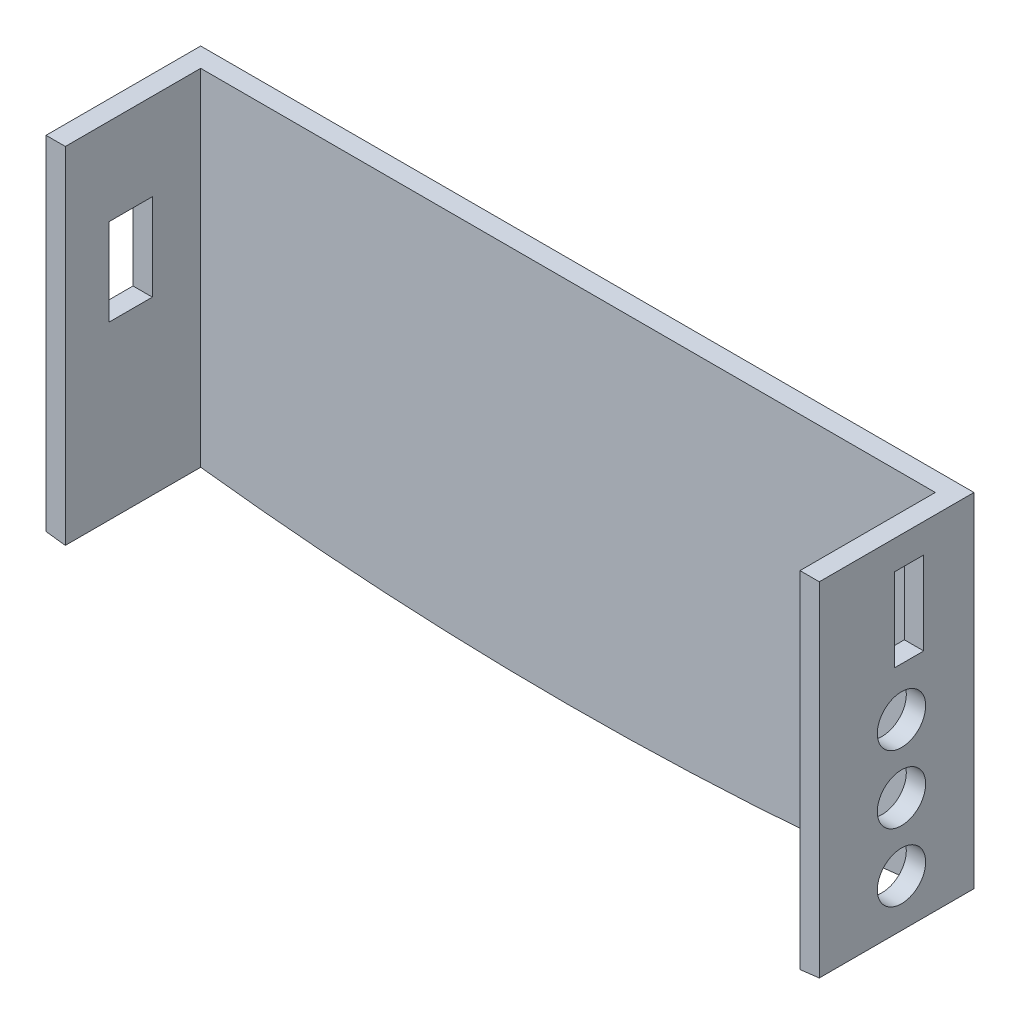
SolidWorks part; units mm, degrees
ref_plane "前视基准面" through (0, 0, 0) normal (0, 0, 1) x (1, 0, 0)
ref_plane "上视基准面" through (0, 0, 0) normal (0, 1, 0) x (1, 0, 0)
ref_plane "右视基准面" through (0, 0, 0) normal (1, 0, 0) x (0, 0, -1)
other "Configuration Table"
sketch "草图1" plane through (0, 0, 0) normal (0, 0, 1) x (1, 0, 0)
  line L1 (-10.4206, -29.1673) -> (-90.4206, -29.1673)
  line L2 (-10.4206, -29.1673) -> (-10.4206, 6.3327)
  line L3 (-10.4206, 6.3327) -> (-90.4206, 6.3327)
  line L4 (-90.4206, -29.1673) -> (-90.4206, 6.3327)
  line L5 (-10.4206, -29.1673) -> (-90.4206, 6.3327) construction
  line L6 (-10.4206, 6.3327) -> (-90.4206, -29.1673) construction
  arc A0 (-90.4206, -29.1673) -> (-10.4206, -29.1673) centre (-50.4206, 290.0866) ccw
  point P0 (-50.4206, -11.4173)
  dimension "D3" = 321.75
  dimension "D1" = 80
  dimension "D2" = 35.5
extrude "凸台-拉伸1" add sketch "草图1" along normal blind 16 contours L4 L1 L2 L3 | L1 A0
shell "抽壳1" thickness 2
sketch "草图2" plane through (-90.4206, 0, 0) normal (-1, 0, 0) x (0, 0, 1)
  line L6 (0, -29.1673) -> (0, 6.3327) construction
  line L7 (7, -2.6673) -> (11.5, -2.6673)
  line L8 (7, -2.6673) -> (7, -11.6673)
  line L9 (7, -11.6673) -> (11.5, -11.6673)
  line L10 (11.5, -2.6673) -> (11.5, -11.6673)
  line L11 (16, 6.3327) -> (0, 6.3327) construction
  dimension "D1" = 4.5
  dimension "D2" = 9
  dimension "D3" = 9
  dimension "D9" = 7
extrude "切除-拉伸3" cut sketch "草图2" against normal up to next
sketch "草图6" plane through (-10.4206, 0, 0) normal (1, 0, 0) x (0, 0, -1)
  line L1 (-8.2, 3.3327) -> (-5.2, 3.3327)
  line L2 (-8.2, 3.3327) -> (-8.2, -5.2673)
  line L3 (-8.2, -5.2673) -> (-5.2, -5.2673)
  line L4 (-5.2, 3.3327) -> (-5.2, -5.2673)
  line L8 (-16, 6.3327) -> (0, 6.3327) construction
  line L11 (0, -29.1673) -> (0, 6.3327) construction
  circle A0 centre (-7.5, -10.2673) radius 2.5
  circle A1 centre (-7.5, -17.2673) radius 2.5
  circle A2 centre (-7.5, -24.2673) radius 2.5
  dimension "D5" = 5
  dimension "D6" = 5
  dimension "D7" = 5
  dimension "D1" = 3
  dimension "D2" = 8.6
  dimension "D3" = 7.5
  dimension "D4" = 3
  dimension "D8" = 5
  dimension "D9" = 7
  dimension "D10" = 7
extrude "切除-拉伸4" cut sketch "草图6" against normal up to next
